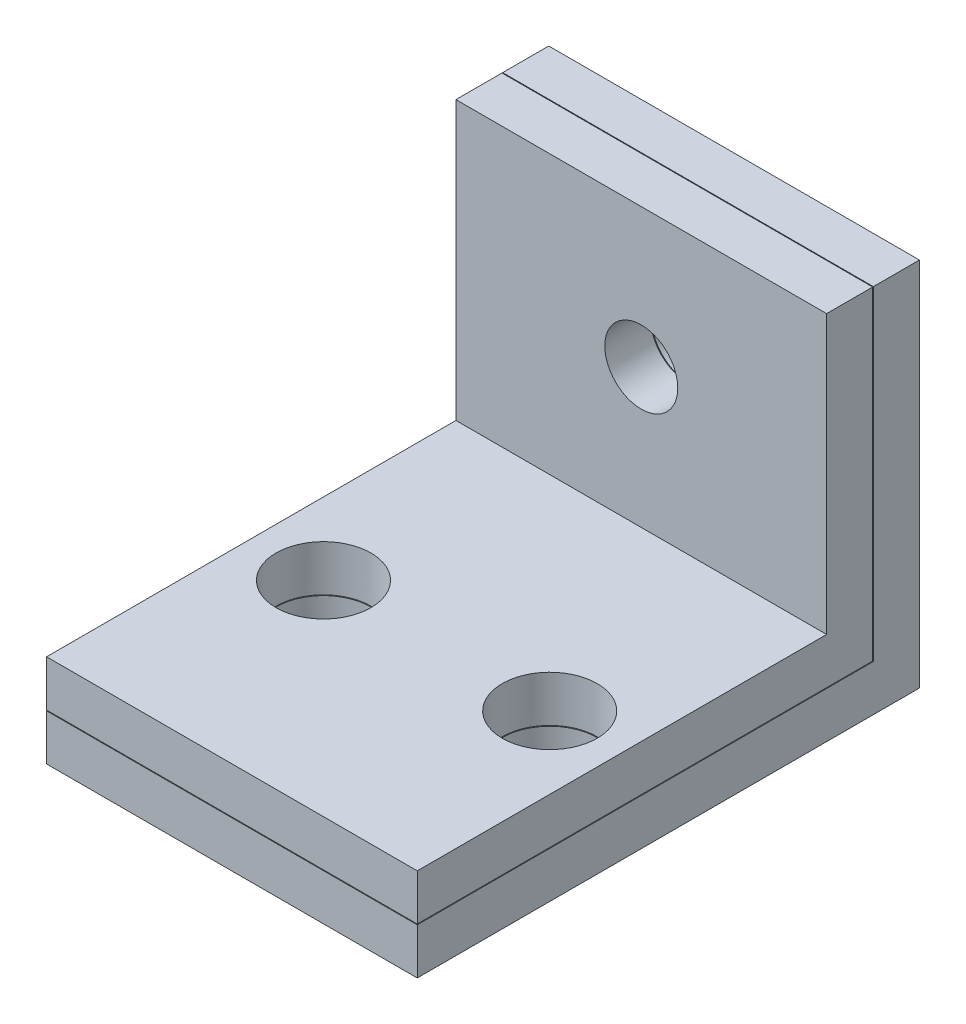
SolidWorks part; units mm, degrees
ref_plane "Alzado" through (0, 0, 0) normal (0, 0, 1) x (1, 0, 0)
ref_plane "Planta" through (0, 0, 0) normal (0, 1, 0) x (1, 0, 0)
ref_plane "Vista lateral" through (0, 0, 0) normal (1, 0, 0) x (0, 0, -1)
sketch "Croquis1" plane through (0, 0, 0) normal (1, 0, 0) x (0, 0, -1)
  line L0 (0, 0) -> (68.82, 0)
  line L1 (68.82, 0) -> (68.82, 50.8)
  line L2 (0, 6.31) -> (62.51, 6.31)
  line L3 (62.51, 6.31) -> (62.51, 50.8)
  line L4 (0, 6.31) -> (0, 0)
  line L5 (62.51, 50.8) -> (68.82, 50.8)
  dimension "D1" = 68.82
  dimension "D2" = 50.8
  dimension "D3" = 6.31
extrude "Saliente-Extruir1" add sketch "Croquis1" along normal blind 50.8
sketch "Croquis2" plane through (50.8, 0, 0) normal (1, 0, 0) x (0, 0, -1)
  line L0 (0, 6.41) -> (62.41, 6.41)
  line L1 (62.41, 6.41) -> (62.41, 50.8)
  line L3 (0, 6.31) -> (0, 9.7762) construction
  line L4 (62.51, 50.8) -> (62.41, 50.8) construction
  line L5 (0, 12.72) -> (56.1, 12.72)
  line L6 (56.1, 12.72) -> (56.1, 50.8)
  line L7 (0, 12.72) -> (0, 6.41)
  line L8 (56.1, 50.8) -> (62.41, 50.8)
  line L9 (62.51, 6.31) -> (0, 6.31) construction
  line L10 (62.51, 50.8) -> (62.51, 6.31) construction
  dimension "D2" = 0.1
  dimension "D3" = 0.1
  dimension "D1" = 6.31
extrude "Saliente-Extruir2" add sketch "Croquis2" against normal blind 50.8 separate body
sketch "Croquis4" plane through (0, 12.72, 0) normal (0, 1, 0) x (1, 0, 0)
  line L0 (0, 28.05) -> (50.8, 28.05) construction
  line L1 (0, 56.1) -> (0, 0) construction
  line L2 (50.8, 56.1) -> (50.8, 0) construction
  line L3 (25.4, 28.05) -> (25.4, 30.6742) construction
  circle A0 centre (9.9, 28.05) radius 6.5
  circle A1 centre (40.9, 28.05) radius 6.5
  dimension "D1" = 13
  dimension "D2" = 13
  dimension "D3" = 15.5
  dimension "D4" = 15.5
extrude "Cortar-Extruir1" cut sketch "Croquis4" against normal blind 97.8
sketch "Croquis5" plane through (0, 0, -56.1) normal (0, 0, 1) x (1, 0, 0)
  line L0 (0, 50.8) -> (0, 12.72) construction
  line L1 (0, 12.72) -> (0, 31.76) construction
  line L2 (0, 31.76) -> (50.8, 31.76) construction
  line L3 (50.8, 50.8) -> (50.8, 12.72) construction
  line L4 (50.8, 31.76) -> (25.4, 31.76) construction
  line L5 (25.4, 31.76) -> (25.4, 50.8) construction
  line L6 (0, 50.8) -> (50.8, 50.8) construction
  circle A0 centre (25.4, 31.76) radius 5
  dimension "D1" = 10
extrude "Cortar-Extruir2" cut sketch "Croquis5" against normal blind 22
